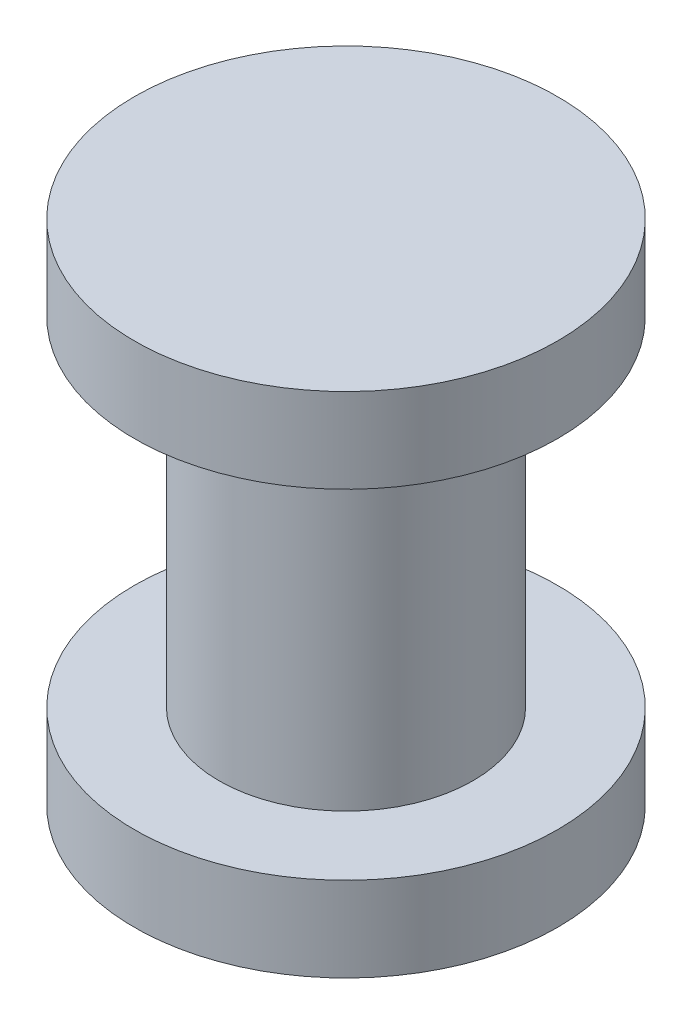
SolidWorks part; units mm, degrees
ref_plane "Front Plane" through (0, 0, 0) normal (0, 0, 1) x (1, 0, 0)
ref_plane "Top Plane" through (0, 0, 0) normal (0, 1, 0) x (1, 0, 0)
ref_plane "Right Plane" through (0, 0, 0) normal (1, 0, 0) x (0, 0, -1)
sketch "Sketch1" plane through (0, 0, 0) normal (0, 0, 1) x (1, 0, 0)
  line L0 (-14.7615, 25.9486) -> (-17.2615, 25.9486)
  line L1 (-14.7615, 25.9486) -> (-14.7615, 19.9486)
  line L2 (-14.7615, 19.9486) -> (-17.2615, 19.9486)
  line L3 (-17.2615, 19.9486) -> (-17.2615, 20.9486)
  line L4 (-17.2615, 20.9486) -> (-16.2615, 20.9486)
  line L5 (-16.2615, 20.9486) -> (-16.2615, 24.9486)
  line L6 (-16.2615, 24.9486) -> (-17.2615, 24.9486)
  line L7 (-17.2615, 24.9486) -> (-17.2615, 25.9486)
  line L8 (-14.7615, 25.9486) -> (-14.7615, 19.9486) construction
  dimension "D1" = 2.5
  dimension "D2" = 2.5
  dimension "D3" = 6
  dimension "D4" = 1.5
  dimension "D5" = 1
  dimension "D6" = 1
revolve "Revolve1" add sketch "Sketch1" angle 360 about L8
